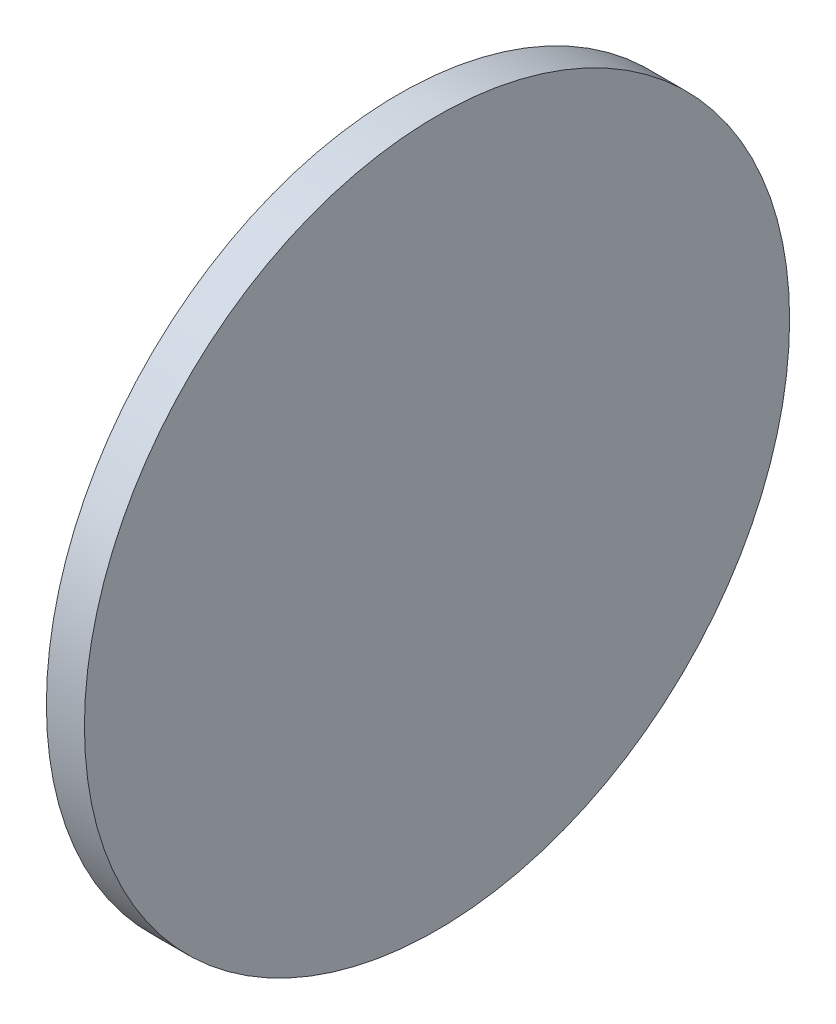
SolidWorks part; units mm, degrees
ref_plane "Front Plane" through (0, 0, 0) normal (0, 0, 1) x (1, 0, 0)
ref_plane "Top Plane" through (0, 0, 0) normal (0, 1, 0) x (1, 0, 0)
ref_plane "Right Plane" through (0, 0, 0) normal (1, 0, 0) x (0, 0, -1)
sketch "Sketch1" plane through (0, 0, 0) normal (0, 0, 1) x (1, 0, 0)
  line L0 (0, 0) -> (6.3462, 0) construction
  line L1 (0, 0) -> (0, 5)
  line L2 (0, 5) -> (0.5, 5)
  line L3 (0.5, 5) -> (0.5, 13.9)
  line L4 (0.5, 13.9) -> (2, 13.9)
  line L5 (2, 13.9) -> (2, 0)
  line L6 (2, 0) -> (0, 0)
  dimension "D1" = 0.5
  dimension "D2" = 1.5
  dimension "D3" = 27.8
  dimension "D4" = 10
revolve "Revolve1" add sketch "Sketch1" angle 360 about L0
